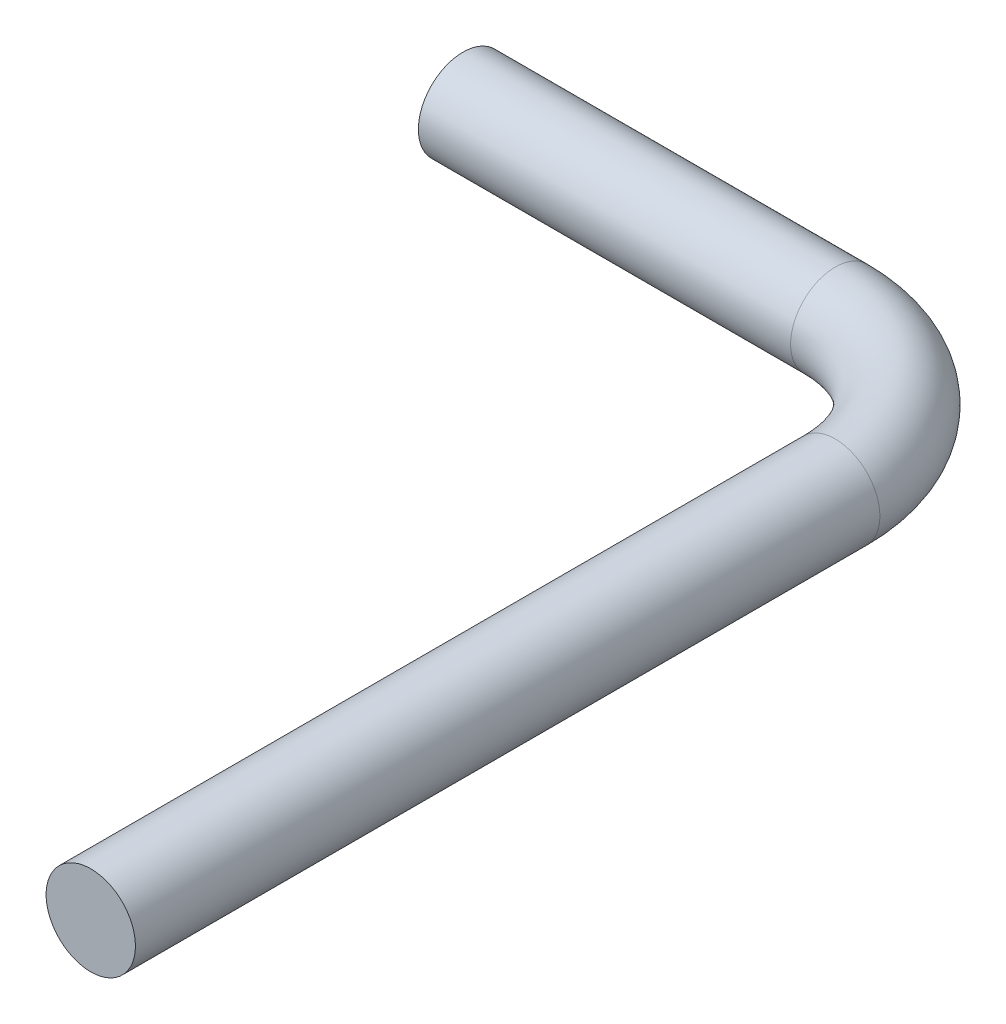
SolidWorks part; units mm, degrees
ref_plane "Alzado" through (0, 0, 0) normal (0, 0, 1) x (1, 0, 0)
ref_plane "Planta" through (0, 0, 0) normal (0, 1, 0) x (1, 0, 0)
ref_plane "Vista lateral" through (0, 0, 0) normal (1, 0, 0) x (0, 0, -1)
sketch "Croquis2" plane through (0, 0, 0) normal (0, 1, 0) x (1, 0, 0)
  line L0 (0, 0) -> (2.5, 0)
  line L1 (3.5, -1) -> (3.5, -6)
  arc A0 (2.5, 0) -> (3.5, -1) centre (2.5, -1) cw
  dimension "D2" = 1
  dimension "D1" = 3.5
  dimension "D3" = 6
sketch "Croquis3" plane through (0, 0, 0) normal (1, 0, 0) x (0, 0, -1)
  circle A0 centre (0, 0) radius 0.3
  dimension "D1" = 0.6
sweep "Barrer1" add profiles "Croquis3" path "Croquis2"
